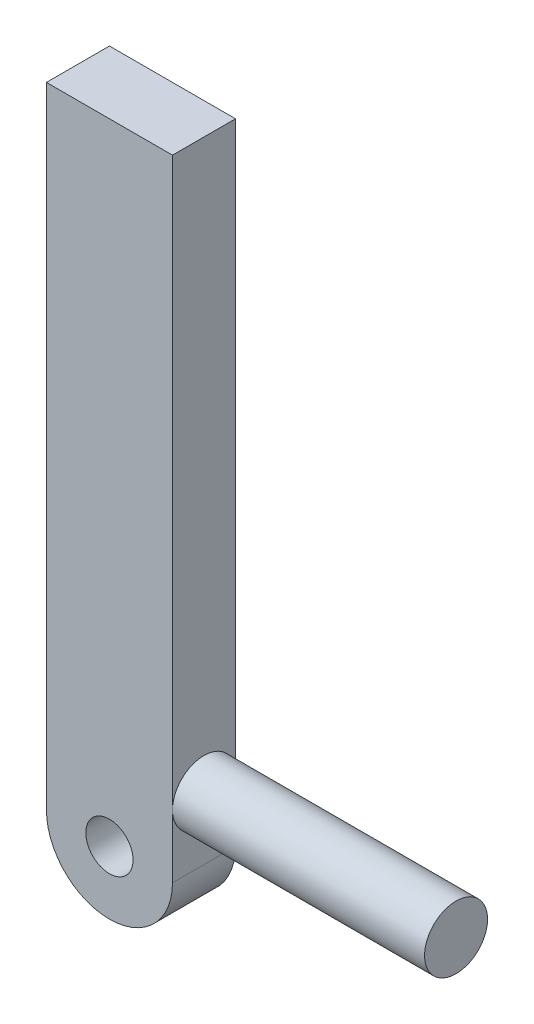
SolidWorks part; units mm, degrees
ref_plane "Front Plane" through (0, 0, 0) normal (0, 0, 1) x (1, 0, 0)
ref_plane "Top Plane" through (0, 0, 0) normal (0, 1, 0) x (1, 0, 0)
ref_plane "Right Plane" through (0, 0, 0) normal (1, 0, 0) x (0, 0, -1)
sketch "Sketch1" plane through (0, 0, 0) normal (0, 0, 1) x (1, 0, 0)
  line L0 (-12.7, 0) -> (-12.7, 127)
  line L1 (-12.7, 127) -> (12.7, 127)
  line L2 (12.7, 127) -> (12.7, 0)
  arc A0 (-12.7, 0) -> (12.7, 0) centre (0, 0) ccw
  circle A1 centre (0, 0) radius 4.7625
  dimension "D1" = 9.525
  dimension "D2" = 25.4
  dimension "D3" = 127
extrude "Boss-Extrude1" add sketch "Sketch1" along normal blind 12.7
sketch "Sketch2" plane through (12.7, 0, 0) normal (1, 0, 0) x (0, 0, -1)
  line L0 (-12.7, 127) -> (0, 127) construction
  line L1 (-12.7, -12.7) -> (0, -12.7) construction
  circle A0 centre (-6.35, 12.7) radius 6.35
  point P2 (0, 0)
  point P5 (-6.35, 127)
  dimension "D2" = 12.7
  dimension "D1" = 19.05
extrude "Boss-Extrude2" add sketch "Sketch2" along normal blind 50.8
